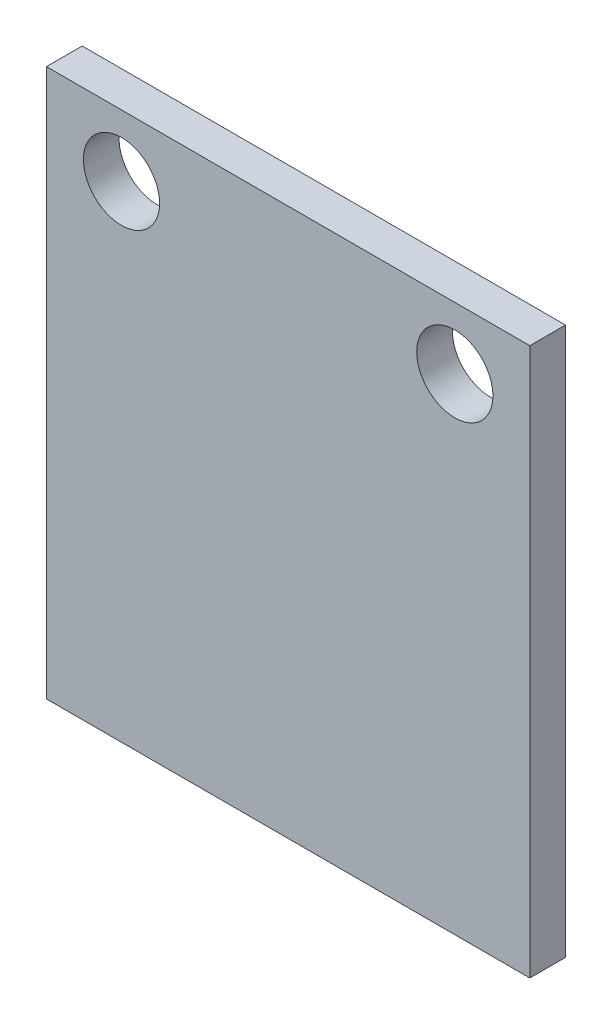
SolidWorks part; units mm, degrees
ref_plane "Спереди" through (0, 0, 0) normal (0, 0, 1) x (1, 0, 0)
ref_plane "Сверху" through (0, 0, 0) normal (0, 1, 0) x (1, 0, 0)
ref_plane "Справа" through (0, 0, 0) normal (1, 0, 0) x (0, 0, -1)
sketch "Эскиз1" plane through (0, 0, 0) normal (0, 0, 1) x (1, 0, 0)
  line L0 (0, -12.65) -> (0, 12.65) construction
  line L1 (-10.15, -11.5) -> (10.15, -11.5)
  line L2 (-10.15, -11.5) -> (-10.15, 11.5)
  line L3 (-10.15, 11.5) -> (10.15, 11.5)
  line L4 (10.15, -11.5) -> (10.15, 11.5)
  line L5 (-10.15, -11.5) -> (10.15, 11.5) construction
  line L6 (-10.15, 11.5) -> (10.15, -11.5) construction
  circle A0 centre (-7, 8.9) radius 1.6
  circle A1 centre (7, 8.9) radius 1.6
  point P0 (0, 0)
  dimension "D4" = 3.2
  dimension "D1" = 20.3
  dimension "D2" = 23
  dimension "D3" = 14
  dimension "D5" = 2.6
extrude "Бобышка-Вытянуть1" add sketch "Эскиз1" along normal blind 1.5
